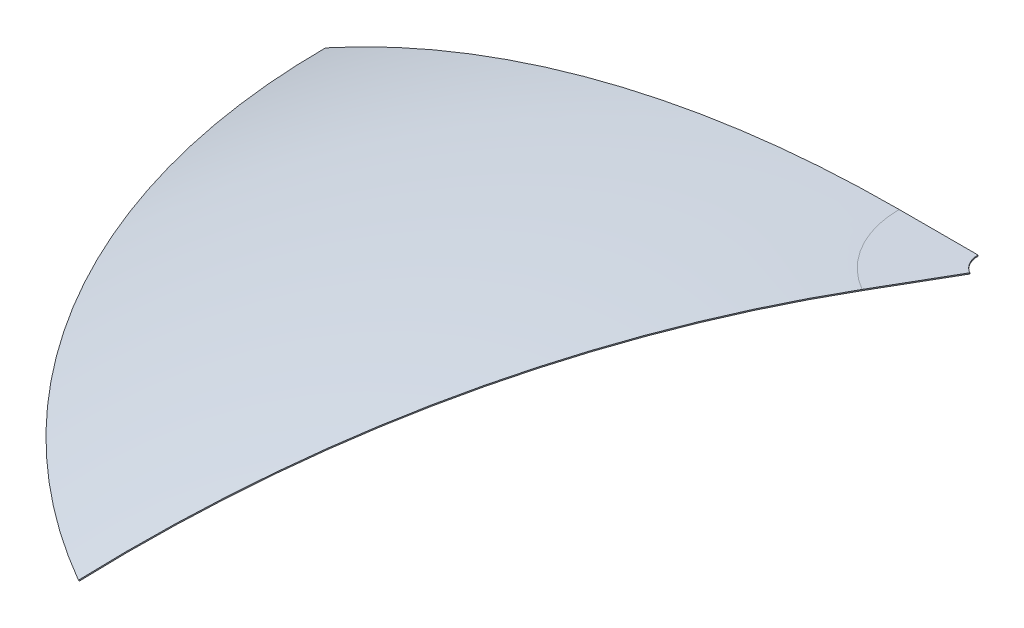
SolidWorks part; units mm, degrees
ref_plane "Front Plane" through (0, 0, 0) normal (0, 0, 1) x (1, 0, 0)
ref_plane "Top Plane" through (0, 0, 0) normal (0, 1, 0) x (1, 0, 0)
ref_plane "Right Plane" through (0, 0, 0) normal (1, 0, 0) x (0, 0, -1)
sketch "Sketch1" plane through (0, 0, 0) normal (0, 0, 1) x (1, 0, 0)
  line L0 (45, 1.5) -> (-45, 1.5) construction
  line L1 (45, 1.5) -> (-45, 1.5) construction
  line L2 (10, 1.5) -> (-10, 1.5) construction
  line L3 (10, 1.5) -> (-10, 1.5) construction
  line L4 (-45, 1.5) -> (-10, 1.5)
  line L6 (-45, 2) -> (-10, 2)
  line L7 (-10, 2) -> (-10, 1.5)
  line L8 (-299.7402, -63.211) -> (-299.5, -63.6495)
  line L9 (0, -998.5) -> (0, 49001.5) construction
  arc A0 (-46.0019, 1.4991) -> (-299.5, -63.6495) centre (-45, -528.1639) ccw construction
  arc A1 (-46.0019, 1.4991) -> (-299.5, -63.6495) centre (-45, -528.1639) ccw
  arc A2 (-45, 1.5) -> (-46.0019, 1.4991) centre (-45, -528.1639) ccw
  arc A3 (-46.0028, 1.9991) -> (-299.7402, -63.211) centre (-45, -528.1639) ccw
  arc A4 (-45, 2) -> (-46.0028, 1.9991) centre (-45, -528.1639) ccw
  point P17 (0, 1.5)
  dimension "D1" = 0.5
  dimension "D2" = 1.0019
  dimension "D3" = 264.4748
  dimension "D4" = 1.0019
  dimension "D5" = 35
revolve "Revolve1" add sketch "Sketch1" angle 60 about L9
sketch "Sketch3" plane through (0, 2, 0) normal (0, 1, 0) x (1, 0, 0)
  line L0 (-10, 0) -> (-5, -8.6603)
  arc A0 (-10, 0) -> (-5, -8.6603) centre (0, 0) ccw construction
  arc A1 (-10, 0) -> (-5, -8.6603) centre (0, 0) ccw
extrude "Boss-Extrude1" [suppressed] add sketch "Sketch3" against normal up to surface (0.5 mm away)
